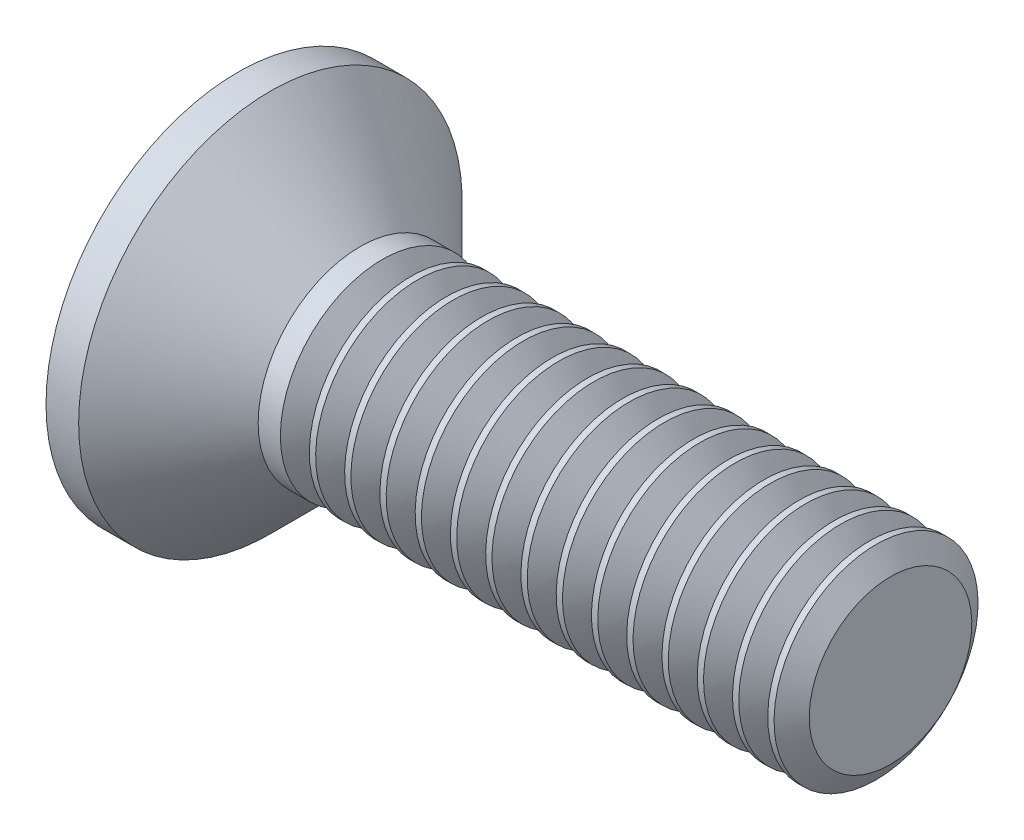
SolidWorks part; units mm, degrees
ref_plane "Plane1" through (0, 0, 0) normal (0, 0, 1) x (1, 0, 0)
ref_plane "Plane2" through (0, 0, 0) normal (0, 1, 0) x (1, 0, 0)
ref_plane "Plane3" through (0, 0, 0) normal (1, 0, 0) x (0, 0, -1)
sketch "BodySke" plane through (0, 0, 0) normal (0, 0, 1) x (1, 0, 0)
  line L0 (0, 0) -> (0, 2.35)
  line L1 (0, 2.35) -> (0.4, 2.35)
  line L2 (1.5, 1.25) -> (8, 1.25)
  line L3 (8, 1.25) -> (8, 0)
  line L4 (8, 0) -> (0, 0)
  line L5 (-6.35, 0) -> (82.55, 0) construction
  line L6 (1.5, -1.25) -> (8, -1.25) construction
  line L7 (0.4, -2.35) -> (1.5, -1.25) construction
  line L8 (0.4, 2.35) -> (1.5, 1.25)
  line L9 (0, -2.35) -> (0.4, -2.35) construction
  line L10 (1.95, 2.8375) -> (1.95, -6.6875) construction
  line L11 (0, 6.35) -> (0, -3.175) construction
  dimension "Diameter" = 2.5
  dimension "Length" = 8
  dimension "Head_ht" = 1.5
  dimension "Head_dia" = 4.7
  dimension "Head_ang" = 90
  dimension "D6" = 0.4
  dimension "Advance" = 0.45
  dimension "Thread_nom" = 8
revolve "Base-Revolve" add sketch "BodySke" angle 360 about L5
cosmetic thread "ThreadCosmetic" [suppressed] parameters "Thread_length"=6.05, "Thread_minor"=1.993
sketch "Sketch2" plane through (0, 0, 0) normal (-1, 0, 0) x (0, 0, 1)
  line L0 (-2.35, -0.4) -> (2.35, -0.4)
  line L1 (-2.35, -0.4) -> (-2.35, 0.4)
  line L2 (2.35, 0.4) -> (-2.35, 0.4)
  line L3 (2.35, 0.4) -> (2.35, -0.4)
  dimension "D1" = 0.4
  dimension "Slot_width" = 0.8
  dimension "D2" = 4.7
  dimension "D3" = 2.35
extrude "Slot" [suppressed] cut sketch "Sketch2" against normal blind 0.7
sketch "Sketch3" plane through (0, 0, 0) normal (-1, 0, 0) x (0, 0, 1)
  line L0 (-0.37, 1.4) -> (0.37, 1.4)
  line L1 (0.37, 1.4) -> (0.37, -1.4)
  line L2 (0.37, -1.4) -> (-0.37, -1.4)
  line L3 (-0.37, -1.4) -> (-0.37, 1.4)
  dimension "D1" = 1.4
  dimension "Cross_dia" = 2.8
  dimension "D2" = 0.37
  dimension "Cross_width" = 0.74
ref_plane "Plane4" through (1.78, 0, 0) normal (-1, 0, 0) x (0, 0, 1)
sketch "Sketch4" plane through (1.78, 0, 0) normal (-1, 0, 0) x (0, 0, 1)
  line L0 (-0.185, 0.185) -> (0.185, 0.185)
  line L3 (0.185, 0.185) -> (0.185, -0.185)
  line L4 (0.185, -0.185) -> (-0.185, -0.185)
  line L5 (-0.185, -0.185) -> (-0.185, 0.185)
  dimension "D1" = 0.37
  dimension "D2" = 0.37
  dimension "D3" = 0.185
  dimension "D4" = 0.185
loft "Cross" cut profiles "Sketch3", "Sketch4"
pattern_circular "CirPattern1" count 2 every 90 about axis through (0, 0, 0) along (1, 0, 0) of "Cross"
sketch "ThdSchSke" plane through (0, 0, 0) normal (0, 0, 1) x (1, 0, 0)
  line L0 (1.95, -0.9965) -> (1.7725, -1.25)
  line L1 (1.95, -0.9965) -> (2.1275, -1.25)
  line L2 (2.1275, -1.25) -> (2.1275, -1.5625)
  line L3 (-3.175, 0) -> (5.1513, 0) construction
  line L5 (2.1275, -1.5625) -> (1.7725, -1.5625)
  line L6 (1.7725, -1.5625) -> (1.7725, -1.25)
  line L7 (0, 2.35) -> (0, -2.35) construction
  dimension "Thread_minor" = 1.993
  dimension "Diameter" = 2.5
  dimension "Start" = 1.95
  dimension "SideAngle" = 55
  dimension "VeeAngle" = 70
  dimension "Overcut" = 3.125
revolve "ThreadSchematic" cut sketch "ThdSchSke" angle 360 about L3
pattern_linear "ThdSchPat" count 15 spacing 0.4321 along (1, 0, 0) of "ThreadSchematic"
equation "\"D1@Sketch3\" = \"Cross_dia@Sketch3\" / 2"
equation "\"D2@Sketch3\" = \"Cross_width@Sketch3\" / 2"
equation "\"D1@Sketch4\" = \"Cross_width@Sketch3\" *.5"
equation "\"D2@Sketch4\" = \"D1@Sketch4\""
equation "\"D4@Sketch4\" = \"D2@Sketch4\" / 2"
equation "\"D3@Sketch4\" = \"D1@Sketch4\" / 2"
equation "\"D1@Sketch2\" = \"Slot_width@Sketch2\" / 2"
equation "\"D2@Sketch2\" = \"Head_dia@BodySke\""
equation "\"D3@Sketch2\" = \"D2@Sketch2\" / 2"
equation "\"Thread_length@ThreadCosmetic\" = ((sgn( (\"Length@BodySke\" - \"Advance@BodySke\" - \"Head_ht@BodySke\" ) - \"Thread_nom@BodySke\" )-1)*( (\"Length@BodySke\" - \"Advance@BodySke\" - \"Head_ht@BodySke\" ) - \"Thread_nom@BodySke\" ))/-2+ \"Thread_nom@BodySke\""
equation "\"Thread_minor@ThdSchSke\" = \"Thread_minor@ThreadCosmetic\""
equation "\"Diameter@ThdSchSke\" = \"Diameter@BodySke\""
equation "\"Overcut@ThdSchSke\" = \"Diameter@BodySke\" * 1.25"
equation "\"Start@ThdSchSke\" = 0.000001 + \"Length@BodySke\" - \"Thread_length@ThreadCosmetic\"  '---Countersunk---"
equation "\"Num_threads@ThdSchPat\" = int( \"Thread_length@ThreadCosmetic\" / \"Advance@BodySke\" + 0.999 )  + 1"
equation "\"Advance@ThdSchPat\" = \"Thread_length@ThreadCosmetic\" /  (\"Num_threads@ThdSchPat\" - 1) 'relax it"
